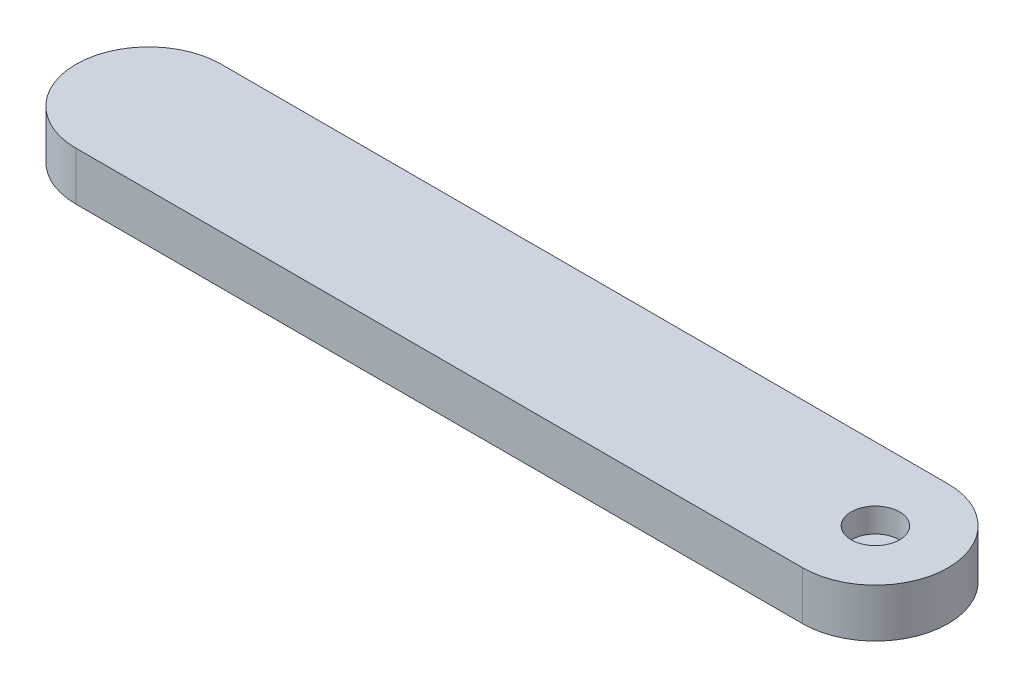
SolidWorks part; units mm, degrees
ref_plane "Front Plane" through (0, 0, 0) normal (0, 0, 1) x (1, 0, 0)
ref_plane "Top Plane" through (0, 0, 0) normal (0, 1, 0) x (1, 0, 0)
ref_plane "Right Plane" through (0, 0, 0) normal (1, 0, 0) x (0, 0, -1)
other "Center of Mass"
sketch "Sketch1" plane through (0, 0, 0) normal (0, 1, 0) x (1, 0, 0)
  line L0 (0, 0) -> (1500, 0) construction
  line L5 (0, 150) -> (1500, 150)
  line L6 (0, -150) -> (1500, -150)
  arc A0 (0, 150) -> (0, -150) centre (0, 0) ccw
  arc A1 (1500, -150) -> (1500, 150) centre (1500, 0) ccw
  point P2 (750, 0)
  dimension "D2" = 150
  dimension "D1" = 1500
extrude "Boss-Extrude1" add sketch "Sketch1" along normal blind 100
sketch "Sketch2" plane through (0, 100, 0) normal (0, 1, 0) x (1, 0, 0)
  circle A0 centre (1500, 0) radius 50
  dimension "D1" = 100
sketch "Sketch3" plane through (0, 0, 0) normal (0, -1, 0) x (1, 0, 0)
  circle A0 centre (0, 0) radius 50
extrude "Boss-Extrude3" add sketch "Sketch3" along normal blind 100
extrude "Cut-Extrude1" cut sketch "Sketch2" against normal blind 50
